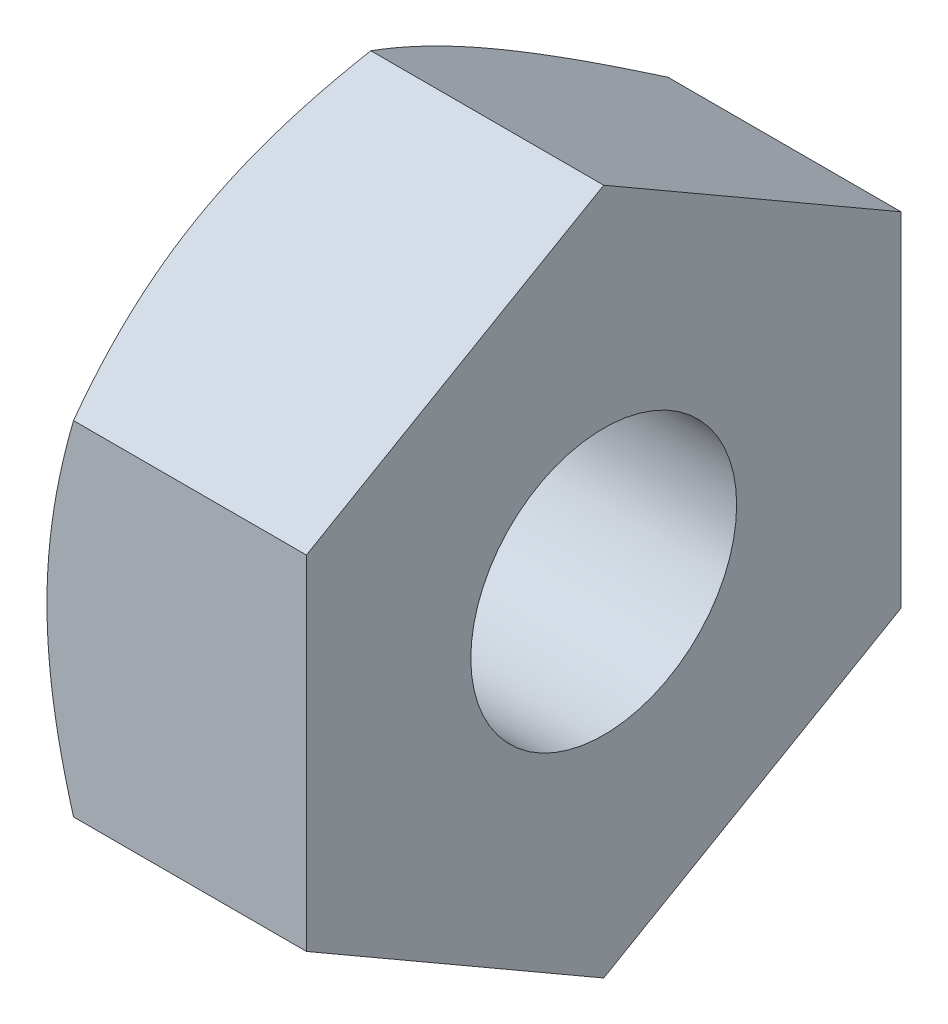
SolidWorks part; units mm, degrees
ref_plane "Front Plane" through (0, 0, 0) normal (0, 0, 1) x (1, 0, 0)
ref_plane "Top Plane" through (0, 0, 0) normal (0, 1, 0) x (1, 0, 0)
ref_plane "Right Plane" through (0, 0, 0) normal (1, 0, 0) x (0, 0, -1)
sketch "Sketch1" plane through (0, 0, 0) normal (1, 0, 0) x (0, 0, -1)
  line L1 (0, 3.1754) -> (-2.75, 1.5877)
  line L2 (-2.75, 1.5877) -> (-2.75, -1.5877)
  line L3 (-2.75, -1.5877) -> (0, -3.1754)
  line L4 (0, -3.1754) -> (2.75, -1.5877)
  line L5 (2.75, -1.5877) -> (2.75, 1.5877)
  line L6 (2.75, 1.5877) -> (0, 3.1754)
  circle A0 centre (0, 0) radius 2.75 construction
extrude "Boss-Extrude1" add sketch "Sketch1" against normal blind 2.4
sketch "Sketch2" plane through (0, 0, 0) normal (0, 0, 1) x (1, 0, 0)
  line L0 (-2.2385, 0) -> (0.6157, 0) construction
  line L1 (-2.4, 2.75) -> (-2.1544, 3.1754)
  line L2 (-2.4, 3.1754) -> (-2.4, 1.5877) construction
  line L3 (-2.4, 3.1754) -> (0, 3.1754) construction
  line L4 (-2.1544, 3.1754) -> (-2.4, 3.1754)
  line L5 (-2.4, 3.1754) -> (-2.4, 2.75)
revolve "Cut-Revolve1" cut sketch "Sketch2" about L0
hole_wizard "Tap1" positions "Sketch4" profile "Sketch3" hole size "M2x0.4" standard "JIS" end condition through all
sketch "Sketch4" plane through (-2.4, 0, 0) normal (-1, 0, 0) x (0, 0, 1)
  point P0 (0, 0)
sketch "Sketch3" plane through (-2.4, 0, 0) normal (0, 1, 0) x (0, 0, 1)
  line L0 (0, 0) -> (0, 2.4)
  line L1 (0, 2.4) -> (1.2295, 2.4)
  line L2 (1.2295, 2.4) -> (1.2295, 0)
  line L5 (1.2295, 0) -> (0, 0)
  line L11 (0, 0) -> (0, 2.4) construction
  dimension "STD_1" = 2.459
  dimension "STL_1" = 2.4
cosmetic thread "Thread1" parameters "M"=3
other "DeleteFace1" [suppressed]
sketch "Sketch5" plane through (0, 0, 0) normal (0, 0, 1) x (1, 0, 0)
  line L0 (0, 0) -> (-2.4, 0) construction
  line L1 (-2.1544, 3.1754) -> (0, 3.1754) construction
  line L2 (-2.4, 0) -> (-1.2, 0)
  line L3 (-2.4, 0) -> (-2.4, 3.1754)
  line L4 (-2.4, 3.1754) -> (-1.2, 3.1754)
  line L5 (-1.2, 0) -> (-1.2, 3.1754)
  dimension "T1" = 1.2
revolve "Cut-Revolve2" [suppressed] cut sketch "Sketch5" about L0
sketch "Sketch6" plane through (0, 0, 0) normal (0, 0, 1) x (1, 0, 0)
  line L0 (-1.2, 2.75) -> (-0.9544, 3.1754)
  line L1 (-1.2, 0) -> (-1.2, 3.1754) construction
  line L2 (-2.4, 3.1754) -> (-1.2, 3.1754) construction
  line L3 (-0.9544, 3.1754) -> (-1.2, 3.1754)
  line L4 (-1.2, 3.1754) -> (-1.2, 2.75)
  line L5 (0, 2.75) -> (-0.2456, 3.1754)
  line L6 (0, 3.1754) -> (0, 1.5877) construction
  line L7 (-0.2456, 3.1754) -> (0, 3.1754)
  line L8 (0, 3.1754) -> (0, 2.75)
  line L9 (-1.687, 0) -> (0.4573, 0) construction
revolve "Cut-Revolve3" [suppressed] cut sketch "Sketch6" about L9
hole_wizard "Tap2" [suppressed] positions "Sketch8" profile "Sketch7" hole size "M2x0.4" standard "JIS"
sketch "Sketch8" plane through (0, 0, 0) normal (1, 0, 0) x (0, 0, -1)
  point P0 (0, 0)
sketch "Sketch7" plane through (0, 0, 0) normal (0, 1, 0) x (0, 0, -1)
  line L0 (0, 0) -> (0, 1.2)
  line L1 (0, 1.2) -> (0.7835, 1.2)
  line L2 (0.7835, 1.2) -> (0.7835, 0)
  line L5 (0.7835, 0) -> (0, 0)
  line L11 (0, 0) -> (0, 1.2) construction
  dimension "STD_2" = 1.567
  dimension "STL_2" = 1.2
cosmetic thread "Thread2" [suppressed] parameters "M"=3
sketch "Sketch9" plane through (0, 0, 0) normal (1, 0, 0) x (0, 0, -1)
  line L0 (-1.375, 2.3816) -> (1.375, -2.3816) construction
  line L1 (0, -3.1754) -> (2.75, -1.5877) construction
